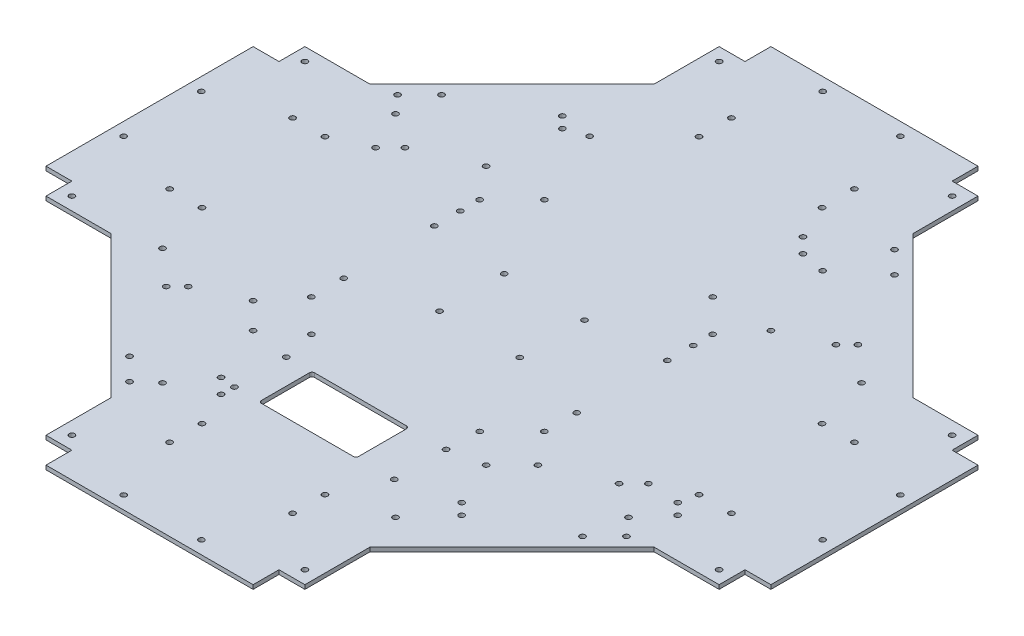
SolidWorks part; units mm, degrees
ref_plane "Front Plane" through (0, 0, 0) normal (0, 0, 1) x (1, 0, 0)
ref_plane "Top Plane" through (0, 0, 0) normal (0, 1, 0) x (1, 0, 0)
ref_plane "Right Plane" through (0, 0, 0) normal (1, 0, 0) x (0, 0, -1)
sketch "Sketch1" plane through (0, 0, 0) normal (0, 1, 0) x (1, 0, 0)
  line L0 (0, -280) -> (100, -280)
  line L1 (100, -280) -> (100, -209.6016)
  line L2 (280, -100) -> (209.6016, -100)
  line L3 (0, 0) -> (0, -280) construction
  line L4 (280, 0) -> (280, -100)
  line L5 (-280, 280) -> (280, 280) construction
  line L6 (-280, 280) -> (-280, -280) construction
  line L7 (-280, -280) -> (280, -280) construction
  line L8 (280, 280) -> (280, -280) construction
  line L9 (-280, 280) -> (280, -280) construction
  line L10 (-280, -280) -> (280, 280) construction
  line L11 (100, -209.6016) -> (209.6016, -100)
  line L12 (-280, 0) -> (-280, -100)
  line L13 (-280, -100) -> (-209.6016, -100)
  line L14 (-209.6016, -100) -> (-100, -209.6016)
  line L15 (-100, -280) -> (-100, -209.6016)
  line L16 (0, -280) -> (-100, -280)
  line L17 (0, 280) -> (-100, 280)
  line L18 (-100, 280) -> (-100, 209.6016)
  line L19 (-100, 209.6016) -> (-209.6016, 100)
  line L20 (-280, 100) -> (-209.6016, 100)
  line L21 (-280, 0) -> (-280, 100)
  line L22 (280, 0) -> (280, 100)
  line L23 (280, 100) -> (209.6016, 100)
  line L24 (209.6016, 100) -> (100, 209.6016)
  line L25 (100, 280) -> (100, 209.6016)
  line L26 (0, 280) -> (100, 280)
  line L27 (111.5258, -219.2889) -> (219.2889, -111.5258) construction
  line L28 (219.2889, -111.5258) -> (247.5732, -139.8101) construction
  line L29 (247.5732, -139.8101) -> (139.8101, -247.5732) construction
  line L30 (139.8101, -247.5732) -> (111.5258, -219.2889) construction
  line L31 (-100, -270) -> (100, -270) construction
  line L32 (-90, -280) -> (-90, 280) construction
  line L33 (-75, -75) -> (75, -75) construction
  line L34 (-75, -75) -> (-75, 75) construction
  line L35 (-75, 75) -> (75, 75) construction
  line L36 (75, -75) -> (75, 75) construction
  line L37 (-75, -75) -> (75, 75) construction
  line L38 (-75, 75) -> (75, -75) construction
  line L39 (-100, -260) -> (100, -260) construction
  line L40 (-280, 40) -> (280, 40) construction
  line L41 (0, 280) -> (0, 0) construction
  line L42 (-280, -90) -> (280, -90) construction
  line L43 (-260, -100) -> (-260, 100) construction
  line L44 (0, 0) -> (-280, 0) construction
  arc A0 (100, -280) -> (280, -100) centre (100, -100) ccw construction
  circle A1 centre (-47.5, -192) radius 2.125
  circle A2 centre (-47.5, -217) radius 2.125
  circle A3 centre (47.5, -217) radius 2.125
  circle A4 centre (47.5, -192) radius 2.125
  circle A5 centre (-192, 47.5) radius 2.125
  circle A6 centre (-217, 47.5) radius 2.125
  circle A7 centre (-192, -47.5) radius 2.125
  circle A8 centre (-217, -47.5) radius 2.125
  circle A9 centre (47.5, 192) radius 2.125
  circle A10 centre (47.5, 217) radius 2.125
  circle A11 centre (-47.5, 192) radius 2.125
  circle A12 centre (-47.5, 217) radius 2.125
  circle A13 centre (192, -47.5) radius 2.125
  circle A14 centre (217, -47.5) radius 2.125
  circle A15 centre (192, 47.5) radius 2.125
  circle A16 centre (217, 47.5) radius 2.125
  circle A17 centre (-90, -270) radius 2.125
  circle A18 centre (-30, -270) radius 2.125
  circle A19 centre (30, -270) radius 2.125
  circle A20 centre (90, -270) radius 2.125
  circle A21 centre (-270, 90) radius 2.125
  circle A22 centre (-270, 30) radius 2.125
  circle A23 centre (-270, -30) radius 2.125
  circle A24 centre (-270, -90) radius 2.125
  circle A25 centre (90, 270) radius 2.125
  circle A26 centre (30, 270) radius 2.125
  circle A27 centre (-30, 270) radius 2.125
  circle A28 centre (-90, 270) radius 2.125
  circle A29 centre (270, -90) radius 2.125
  circle A30 centre (270, -30) radius 2.125
  circle A31 centre (270, 30) radius 2.125
  circle A32 centre (270, 90) radius 2.125
  circle A33 centre (-90, -250) radius 2.125
  circle A34 centre (-90, -180) radius 2.125
  circle A35 centre (-90, -110) radius 2.125
  circle A36 centre (-90, -40) radius 2.125
  circle A37 centre (-90, 30) radius 2.125
  circle A38 centre (-90, 50) radius 2.125
  circle A39 centre (-90, 100) radius 2.125 construction
  circle A40 centre (-90, 150) radius 2.125
  circle A41 centre (-90, 200) radius 2.125 construction
  circle A42 centre (-90, 250) radius 2.125
  circle A43 centre (90, -250) radius 2.125
  circle A44 centre (90, -180) radius 2.125
  circle A45 centre (90, -110) radius 2.125
  circle A46 centre (90, -40) radius 2.125
  circle A47 centre (90, 30) radius 2.125
  circle A48 centre (90, 50) radius 2.125
  circle A49 centre (90, 100) radius 2.125 construction
  circle A50 centre (90, 150) radius 2.125
  circle A51 centre (90, 200) radius 2.125 construction
  circle A52 centre (90, 250) radius 2.125
  circle A53 centre (-250, -90) radius 2.125
  circle A54 centre (-180, -90) radius 2.125
  circle A55 centre (-110, -90) radius 2.125
  circle A56 centre (-110, 90) radius 2.125
  circle A57 centre (-180, 90) radius 2.125
  circle A58 centre (-250, 90) radius 2.125
  circle A59 centre (110, -90) radius 2.125
  circle A60 centre (180, -90) radius 2.125
  circle A61 centre (250, -90) radius 2.125
  circle A62 centre (110, 90) radius 2.125
  circle A63 centre (180, 90) radius 2.125
  circle A64 centre (250, 90) radius 2.125
  point P33 (0, 0)
  point P68 (0, 0)
  point P107 (0, 0)
  dimension "D10" = 25
  dimension "4.25" = 4.25
  dimension "D11" = 4.25
  dimension "D16" = 4.25
  dimension "D24" = 4.25
  dimension "D28" = 4.25
  dimension "D32" = 4.25
  dimension "D1" = 560
  dimension "D2" = 90
  dimension "D3" = 280
  dimension "D4" = 4
  dimension "D5" = 100
  dimension "D6" = 155
  dimension "D7" = 152.4
  dimension "D8" = 15
  dimension "D9" = 40
  dimension "D12" = 47.5
  dimension "D13" = 63
  dimension "D15" = 10
  dimension "D17" = 10
  dimension "D18" = 76.2
  dimension "D19" = 150
  dimension "D20" = 150
  dimension "D23" = 10
  dimension "D25" = 10
  dimension "D26" = 300
  dimension "D29" = 10
  dimension "D31" = 20
  dimension "D33" = 10
  dimension "D21" = 4
  dimension "D27" = 5
  dimension "D30" = 5
  dimension "D34" = 3
  dimension "D14" = 4
  dimension "D22" = 4
extrude "Boss-Extrude1" add sketch "Sketch1" along normal blind 3.175 contours L26 L17 L18 L19 L20 L21 L12 L13 L14 L15 L16 L0 L1 L11 L2 L4 L22 L23 L24 L25
sketch "Sketch2" plane through (0, 3.175, 0) normal (0, 1, 0) x (1, 0, 0)
  line L0 (0, 25.5202) -> (0, -25) construction
  line L1 (-31, -25) -> (31, -25) construction
  line L2 (-31, -25) -> (-31, 25) construction
  line L3 (-31, 25) -> (31, 25) construction
  line L4 (31, -25) -> (31, 25) construction
  line L5 (-31, -25) -> (31, 25) construction
  line L6 (-31, 25) -> (31, -25) construction
  line L7 (75, -75) -> (75, 75) construction
  line L8 (-75, -75) -> (75, -75) construction
  line L9 (-75, -75) -> (-75, 75) construction
  line L10 (-75, 75) -> (75, 75) construction
  line L11 (75, -75) -> (75, 75) construction
  line L12 (-75, -75) -> (75, -75) construction
  line L13 (-75, -75) -> (-75, 75) construction
  line L14 (-75, 75) -> (75, 75) construction
  line L15 (-90, 270) -> (-90, -270) construction
  line L16 (-270, 90) -> (270, 90) construction
  line L17 (-40.0349, -135) -> (34.9651, -135) construction
  line L18 (-40.0349, -155.5) -> (34.9651, -155.5)
  line L19 (-40.0349, -155.5) -> (-40.0349, -114.5)
  line L20 (-40.0349, -114.5) -> (34.9651, -114.5)
  line L21 (34.9651, -155.5) -> (34.9651, -114.5)
  line L22 (-40.0349, -155.5) -> (34.9651, -114.5) construction
  line L23 (-40.0349, -114.5) -> (34.9651, -155.5) construction
  line L24 (153.737, -71.0118) -> (187.3311, -37.4177) construction
  line L25 (128.2843, -167.1751) -> (80.1718, -119.0627) construction
  line L26 (92.9289, -202.5305) -> (202.5305, -92.9289)
  line L27 (92.9289, -202.5305) -> (202.5305, -92.9289) construction
  line L28 (170.0036, -125.4558) -> (128.4969, -83.9492) construction
  circle A0 centre (-31, 25) radius 2.125
  circle A1 centre (-31, -25) radius 2.125
  circle A2 centre (31, -25) radius 2.125
  circle A3 centre (31, 25) radius 2.125
  circle A4 centre (-90, 65) radius 2.125
  circle A5 centre (-65, 90) radius 2.125
  circle A6 centre (65, 90) radius 2.125
  circle A7 centre (90, 65) radius 2.125
  circle A8 centre (90, -65) radius 2.125
  circle A9 centre (65, -90) radius 2.125
  circle A10 centre (-65, -90) radius 2.125
  circle A11 centre (-90, -65) radius 2.125
  circle A12 centre (64.0651, -115) radius 2.125
  circle A13 centre (64.0651, -155) radius 2.125
  circle A14 centre (-59.4349, -115) radius 2.125
  circle A15 centre (-59.4349, -155) radius 2.125
  circle A16 centre (174.9533, -120.5061) radius 2.125
  circle A17 centre (191.9239, -103.5355) radius 2.125
  circle A18 centre (153.737, -71.0118) radius 2.125
  circle A19 centre (165.0507, -59.6981) radius 2.125
  circle A20 centre (-71.0118, -153.737) radius 2.125
  circle A21 centre (-59.6981, -165.0507) radius 2.125
  circle A22 centre (-120.5061, -174.9533) radius 2.125
  circle A23 centre (-103.5355, -191.9239) radius 2.125
  circle A24 centre (-153.737, 71.0118) radius 2.125
  circle A25 centre (-165.0507, 59.6981) radius 2.125
  circle A26 centre (-174.9533, 120.5061) radius 2.125
  circle A27 centre (-191.9239, 103.5355) radius 2.125
  circle A28 centre (71.0118, 153.737) radius 2.125
  circle A29 centre (59.6981, 165.0507) radius 2.125
  circle A30 centre (120.5061, 174.9533) radius 2.125
  circle A31 centre (103.5355, 191.9239) radius 2.125
  circle A32 centre (114.1421, -153.033) radius 2.125
  circle A33 centre (105.6569, -144.5477) radius 2.125
  circle A34 centre (-144.5477, -105.6569) radius 2.125
  circle A35 centre (-153.033, -114.1421) radius 2.125
  circle A36 centre (-105.6569, 144.5477) radius 2.125
  circle A37 centre (-114.1421, 153.033) radius 2.125
  circle A38 centre (144.5477, 105.6569) radius 2.125
  circle A39 centre (153.033, 114.1421) radius 2.125
  circle A40 centre (197.5807, -69.5944) radius 2.125
  circle A41 centre (189.0955, -61.1091) radius 2.125
  point P0 (0, 0)
  point P28 (-2.5349, -135)
  point P43 (0, 0)
  point P94 (0, 0)
  point P113 (0, 0)
  dimension "D3" = 4.25
  dimension "D4" = 4.25
  dimension "D5" = 4.25
  dimension "D7" = 4.25
  dimension "D13" = 4.25
  dimension "D16" = 4.25
  dimension "D20" = 4.25
  dimension "D22" = 4.25
  dimension "D25" = 4.25
  dimension "D26" = 53.85
  dimension "D27" = 4.25
  dimension "D31" = 4.25
  dimension "D32" = 4.25
  dimension "D1" = 62
  dimension "D2" = 50
  dimension "D6" = 10
  dimension "D8" = 10
  dimension "D10" = 41
  dimension "D11" = 75
  dimension "D12" = 135
  dimension "D14" = 20
  dimension "D15" = 66.6
  dimension "D17" = 19.4
  dimension "D18" = 20
  dimension "D21" = 116
  dimension "D23" = 24
  dimension "D24" = 50
  dimension "D28" = 16
  dimension "D30" = 50
  dimension "D33" = 12
  dimension "D34" = 20
  dimension "D36" = 59
  dimension "D19" = 10
  dimension "D9" = 4
  dimension "D29" = 4
  dimension "D35" = 4
extrude "Cut-Extrude1" cut sketch "Sketch2" against normal through all
fillet "Fillet1" radius 2 4 edges at (34.9651, 1.5875, 114.5) (34.9651, 1.5875, 155.5) (-40.0349, 1.5875, 155.5) (-40.0349, 1.5875, 114.5)
sketch "Sketch3" plane through (0, 3.175, 0) normal (0, 1, 0) x (1, 0, 0)
  line L0 (-100, -280) -> (-100, -209.6016) construction
  line L1 (80, -260) -> (100, -260)
  line L2 (80, -260) -> (80, -280)
  line L3 (80, -280) -> (100, -280)
  line L4 (100, -260) -> (100, -280)
  line L5 (80, -260) -> (100, -280) construction
  line L6 (80, -280) -> (100, -260) construction
  line L7 (-80, -260) -> (-100, -260)
  line L8 (-80, -260) -> (-80, -280)
  line L9 (-80, -280) -> (-100, -280)
  line L10 (-100, -260) -> (-100, -280)
  line L11 (-80, -260) -> (-100, -280) construction
  line L12 (-80, -280) -> (-100, -260) construction
  line L13 (100, -280) -> (-100, -280) construction
  line L14 (-260, 80) -> (-280, 80)
  line L15 (-260, 80) -> (-260, 100)
  line L16 (-260, 100) -> (-280, 100)
  line L17 (-280, 80) -> (-280, 100)
  line L18 (-260, -80) -> (-280, -80)
  line L19 (-260, -80) -> (-260, -100)
  line L20 (-260, -100) -> (-280, -100)
  line L21 (-280, -80) -> (-280, -100)
  line L22 (80, 260) -> (80, 280)
  line L23 (80, 260) -> (100, 260)
  line L24 (100, 260) -> (100, 280)
  line L25 (80, 280) -> (100, 280)
  line L26 (-80, 260) -> (-80, 280)
  line L27 (-80, 260) -> (-100, 260)
  line L28 (-100, 260) -> (-100, 280)
  line L29 (-80, 280) -> (-100, 280)
  line L30 (260, -80) -> (280, -80)
  line L31 (260, -80) -> (260, -100)
  line L32 (260, -100) -> (280, -100)
  line L33 (280, -80) -> (280, -100)
  line L34 (260, 80) -> (280, 80)
  line L35 (260, 80) -> (260, 100)
  line L36 (260, 100) -> (280, 100)
  line L37 (280, 80) -> (280, 100)
  point P0 (90, -270)
  point P7 (-90, -270)
  point P44 (0, 0)
extrude "Cut-Extrude2" cut sketch "Sketch3" against normal through all
